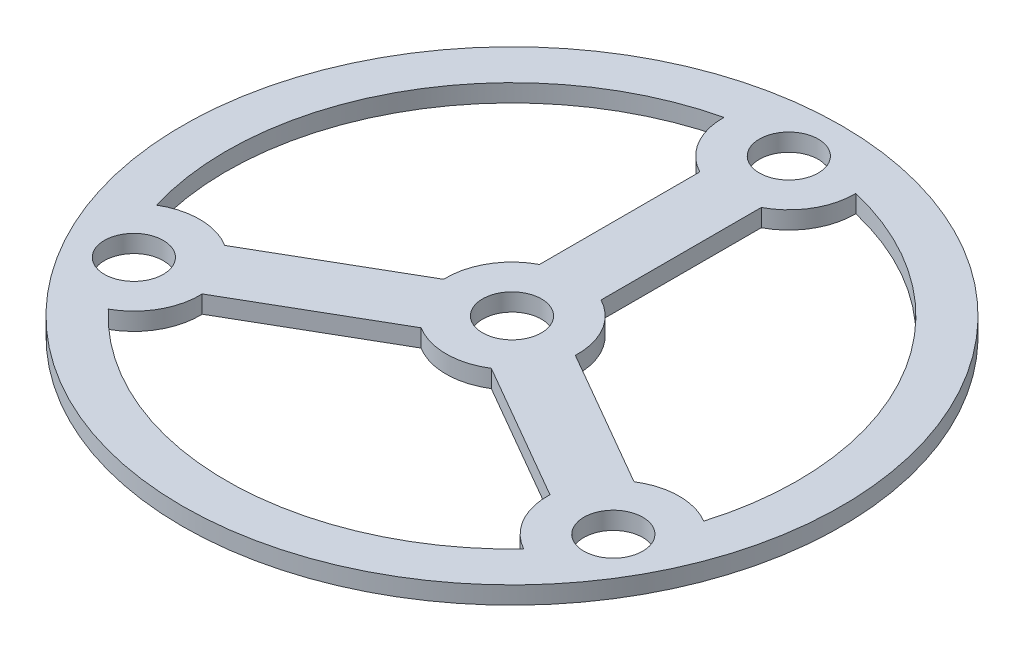
SolidWorks part; units mm, degrees
ref_plane "Front Plane" through (0, 0, 0) normal (0, 0, 1) x (1, 0, 0)
ref_plane "Top Plane" through (0, 0, 0) normal (0, 1, 0) x (1, 0, 0)
ref_plane "Right Plane" through (0, 0, 0) normal (1, 0, 0) x (0, 0, -1)
sketch "Sketch1" plane through (0, 0, 0) normal (0, 1, 0) x (1, 0, 0)
  circle A0 centre (0, 0) radius 37.5
  arc A1 (-7.499, 31.623) -> (-31.1358, -9.3172) centre (0, 0) ccw
  arc A2 (-7.499, 31.623) -> (7.499, 31.623) centre (0, 31.5) ccw
  circle A3 centre (0, 31.5) radius 3.35
  arc A4 (31.1358, -9.3172) -> (23.6368, -22.3058) centre (27.2798, -15.75) ccw
  circle A5 centre (27.2798, -15.75) radius 3.35
  arc A6 (-23.6368, -22.3058) -> (-31.1358, -9.3172) centre (-27.2798, -15.75) ccw
  circle A7 centre (-27.2798, -15.75) radius 3.35
  arc A8 (31.1358, -9.3172) -> (7.499, 31.623) centre (0, 0) ccw
  arc A9 (-23.6368, -22.3058) -> (23.6368, -22.3058) centre (0, 0) ccw
  point P18 (0, 0)
  dimension "D1" = 75
  dimension "D2" = 5
  dimension "D3" = 6.7
  dimension "D4" = 15
  dimension "D5" = 31.5
  dimension "D6" = 3
extrude "Boss-Extrude1" add sketch "Sketch1" along normal blind 2
sketch "Sketch2" plane through (0, 0, 0) normal (0, 1, 0) x (1, 0, 0)
  line L0 (3.5, 6.6332) -> (3.5, 31.5)
  line L1 (-7.4946, -0.2855) -> (-29.0298, -12.7189)
  line L2 (-3.9946, -6.3477) -> (-25.5298, -18.7811)
  line L3 (-1.75, 3.0311) -> (-1.675, 2.9012)
  line L4 (-29.0298, -12.7189) -> (-28.9548, -12.8488)
  line L5 (-25.6048, -18.6512) -> (-25.5298, -18.7811)
  line L6 (1.675, -2.9012) -> (1.75, -3.0311)
  line L7 (-3.5, 6.6332) -> (-3.5, 31.5)
  line L8 (3.5, 31.5) -> (3.35, 31.5)
  line L9 (-3.35, 31.5) -> (-3.5, 31.5)
  line L10 (3.9946, -6.3477) -> (25.5298, -18.7811)
  line L11 (7.4946, -0.2855) -> (29.0298, -12.7189)
  line L12 (25.5298, -18.7811) -> (25.6048, -18.6512)
  line L13 (28.9548, -12.8488) -> (29.0298, -12.7189)
  circle A0 centre (0, 0) radius 7.5
  circle A1 centre (0, 0) radius 3.35
  arc A2 (-3.35, 31.5) -> (3.35, 31.5) centre (0, 31.5) ccw
  arc A3 (-25.6048, -18.6512) -> (-28.9548, -12.8488) centre (-27.2798, -15.75) ccw
  arc A4 (28.9548, -12.8488) -> (25.6048, -18.6512) centre (27.2798, -15.75) ccw
  point P32 (0, 0)
  point P34 (0, 0)
  dimension "D1" = 6.7
  dimension "D2" = 15
  dimension "D3" = 0.1299
  dimension "D4" = 3
extrude "Boss-Extrude2" add sketch "Sketch2" along normal blind 2
